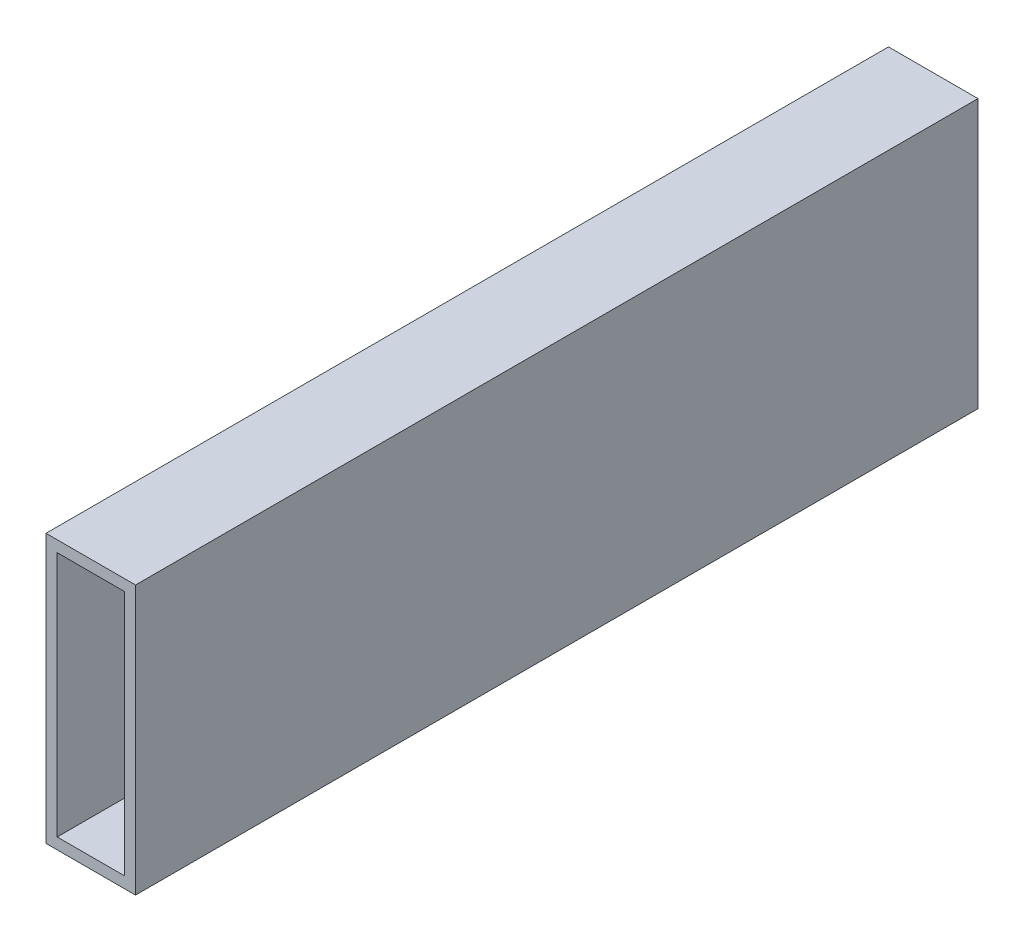
SolidWorks part; units mm, degrees
ref_plane "Front Plane" through (0, 0, 0) normal (0, 0, 1) x (1, 0, 0)
ref_plane "Top Plane" through (0, 0, 0) normal (0, 1, 0) x (1, 0, 0)
ref_plane "Right Plane" through (0, 0, 0) normal (1, 0, 0) x (0, 0, -1)
sketch "Sketch1" plane through (0, 0, 0) normal (0, 0, 1) x (1, 0, 0)
  line L0 (0, 38.1) -> (0, 34.925) construction
  line L1 (-12.7, 38.1) -> (12.7, 38.1)
  line L2 (-12.7, 38.1) -> (-12.7, -38.1)
  line L3 (-12.7, -38.1) -> (12.7, -38.1)
  line L4 (12.7, 38.1) -> (12.7, -38.1)
  line L5 (-12.7, 38.1) -> (12.7, -38.1) construction
  line L6 (-12.7, -38.1) -> (12.7, 38.1) construction
  line L7 (-9.525, 34.925) -> (9.525, 34.925)
  line L8 (-9.525, 34.925) -> (-9.525, -34.925)
  line L9 (-9.525, -34.925) -> (9.525, -34.925)
  line L10 (9.525, 34.925) -> (9.525, -34.925)
  line L11 (9.525, 0) -> (12.7, 0) construction
  line L12 (-9.525, 0) -> (-12.7, 0) construction
  line L13 (0, -34.925) -> (0, -38.1) construction
  point P0 (0, 0)
  dimension "D1" = 76.2
  dimension "D2" = 25.4
  dimension "D3" = 3.175
extrude "Boss-Extrude1" add sketch "Sketch1" along normal blind 239.014
